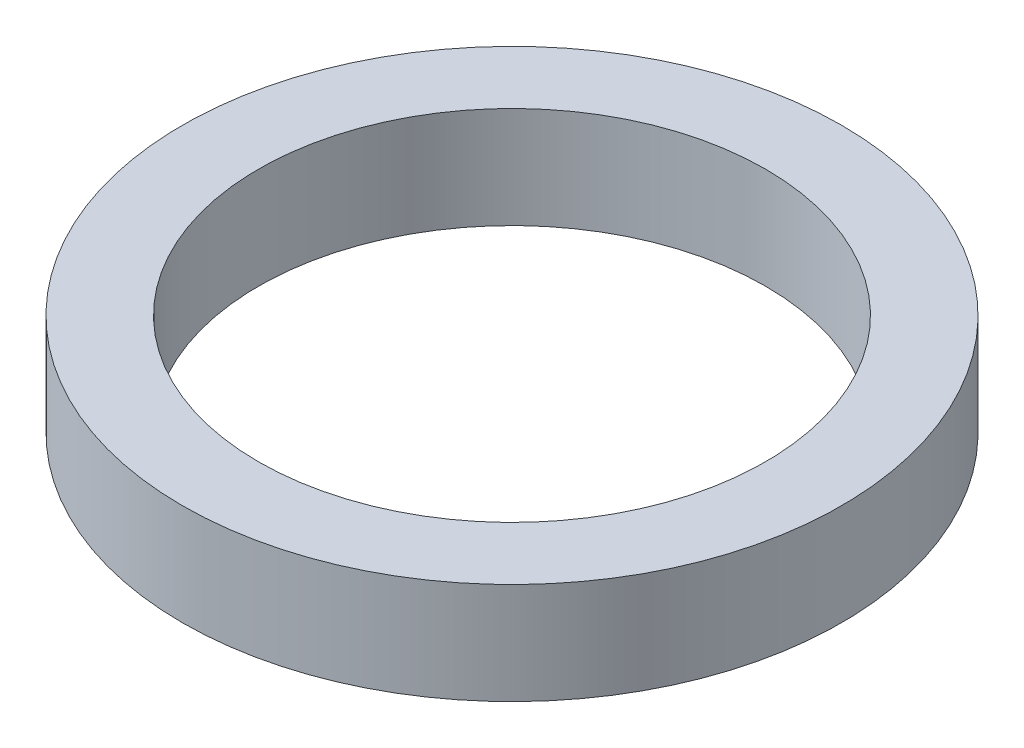
SolidWorks part; units mm, degrees
ref_plane "Front Plane" through (0, 0, 0) normal (0, 0, 1) x (1, 0, 0)
ref_plane "Top Plane" through (0, 0, 0) normal (0, 1, 0) x (1, 0, 0)
ref_plane "Right Plane" through (0, 0, 0) normal (1, 0, 0) x (0, 0, -1)
sketch "Sketch1" plane through (0, 0, 0) normal (0, 1, 0) x (1, 0, 0)
  circle A0 centre (0, 0) radius 3.5
  circle A1 centre (0, 0) radius 2.5
  dimension "D1" = 7
  dimension "D2" = 5
extrude "Boss-Extrude1" [suppressed] add sketch "Sketch1" along normal blind 6
sketch "Sketch2" plane through (0, 0, 0) normal (0, 1, 0) x (1, 0, 0)
  circle A0 centre (0, 0) radius 7.5
  circle A1 centre (0, 0) radius 10
  dimension "D1" = 15
  dimension "D2" = 20
extrude "Boss-Extrude2" [suppressed] add sketch "Sketch2" along normal blind 0.5
sketch "Sketch3" plane through (0, 0, 0) normal (0, 1, 0) x (1, 0, 0)
  circle A0 centre (0, 0) radius 5
  circle A1 centre (0, 0) radius 6.5
  dimension "D1" = 10
  dimension "D2" = 13
extrude "Boss-Extrude3" add sketch "Sketch3" along normal blind 2
